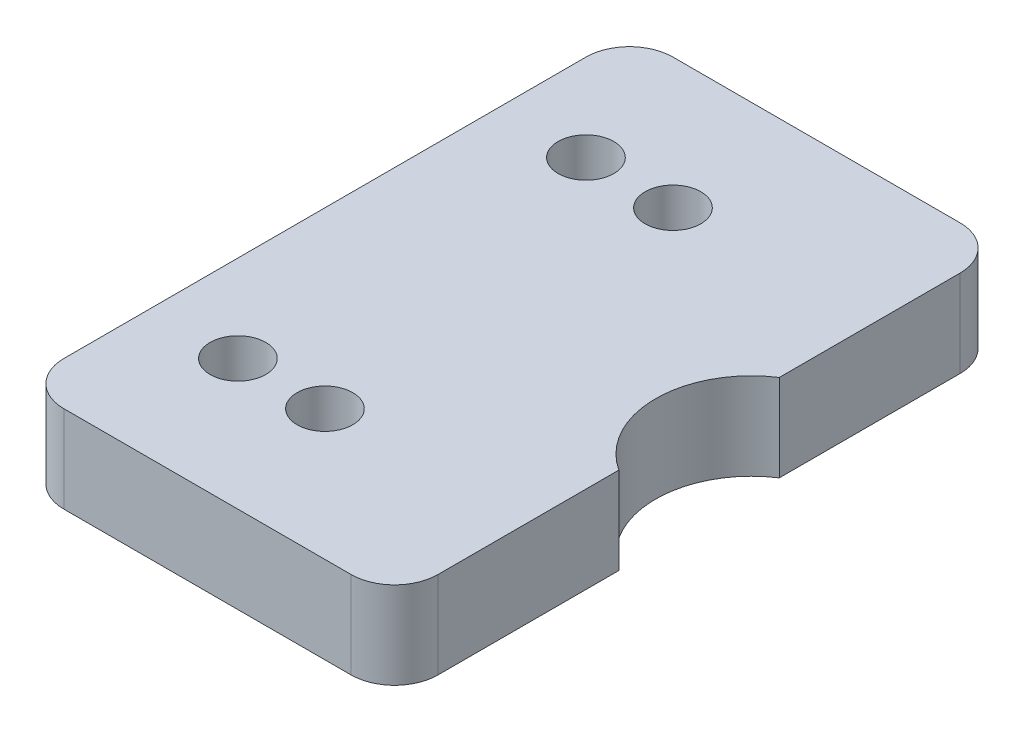
SolidWorks part; units mm, degrees
ref_plane "Front Plane" through (0, 0, 0) normal (0, 0, 1) x (1, 0, 0)
ref_plane "Top Plane" through (0, 0, 0) normal (0, 1, 0) x (1, 0, 0)
ref_plane "Right Plane" through (0, 0, 0) normal (1, 0, 0) x (0, 0, -1)
sketch "Sketch1" plane through (0, 0, 0) normal (0, 1, 0) x (1, 0, 0)
  line L0 (54.61, 32.7412) -> (54.61, 0)
  line L1 (0, 0) -> (54.61, 0)
  line L2 (0, 0) -> (0, 88.9)
  line L3 (0, 88.9) -> (54.61, 88.9)
  line L4 (54.61, 0) -> (54.61, 88.9) construction
  line L5 (54.61, 56.1588) -> (54.61, 88.9)
  line L6 (0, 44.45) -> (62.23, 44.45) construction
  line L7 (0, 69.85) -> (54.61, 69.85) construction
  arc A1 (54.61, 56.1588) -> (54.61, 32.7412) centre (62.23, 44.45) ccw
  circle A2 centre (12.7, 69.85) radius 4.064
  circle A3 centre (25.4, 69.85) radius 4.064
  circle A4 centre (25.4, 19.05) radius 4.064
  circle A5 centre (12.7, 19.05) radius 4.064
  point P15 (14.3843, 79.1165)
  dimension "D3" = 7.62
  dimension "D4" = 13.97
  dimension "D5" = 8.128
  dimension "D6" = 8.128
  dimension "D1" = 88.9
  dimension "D2" = 54.61
  dimension "D7" = 19.05
  dimension "D8" = 12.7
  dimension "D9" = 12.7
extrude "Boss-Extrude1" add sketch "Sketch1" along normal blind 12.7
fillet "Fillet1" radius 6.35 4 edges at (0, 6.35, -88.9) (54.61, 6.35, -88.9) (0, 6.35, 0) (54.61, 6.35, 0)
